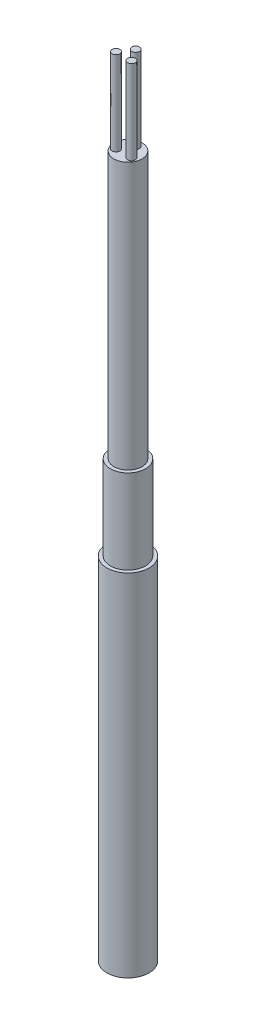
SolidWorks part; units mm, degrees
ref_plane "Front Plane" through (0, 0, 0) normal (0, 0, 1) x (1, 0, 0)
ref_plane "Top Plane" through (0, 0, 0) normal (0, 1, 0) x (1, 0, 0)
ref_plane "Right Plane" through (0, 0, 0) normal (1, 0, 0) x (0, 0, -1)
sketch "SK Stainless sheath" plane through (0, 0, 0) normal (0, 1, 0) x (1, 0, 0)
  circle A0 centre (0, 0) radius 3
extrude "Stainless sheath" add sketch "SK Stainless sheath" along normal blind 50 separate body
sketch "SK Sleeve" plane through (0, 0, 0) normal (0, 1, 0) x (1, 0, 0)
  circle A0 centre (0, 0) radius 2.5
extrude "Sleeve" add sketch "SK Sleeve" along normal blind 12 from offset 50 separate body
sketch "SK Cable" plane through (0, 0, 0) normal (0, 1, 0) x (1, 0, 0)
  circle A0 centre (0, 0) radius 2
extrude "Cable" add sketch "SK Cable" along normal blind 38 from offset 62 separate body
sketch "SK Wire red VDD" plane through (0, 0, 0) normal (0, 1, 0) x (1, 0, 0)
  circle A0 centre (-1.1, -0.6) radius 0.55
extrude "Wire red VDD" add sketch "SK Wire red VDD" along normal blind 12 from offset 100 separate body
sketch "SK Wire black GND" plane through (0, 0, 0) normal (0, 1, 0) x (1, 0, 0)
  circle A0 centre (1.1, -0.6) radius 0.55
extrude "Wire black GND" add sketch "SK Wire black GND" along normal blind 12 from offset 100 separate body
sketch "SK Wire yellow DQ" plane through (0, 0, 0) normal (0, 1, 0) x (1, 0, 0)
  circle A0 centre (0, 1.1) radius 0.55
extrude "Wire yellow DQ" add sketch "SK Wire yellow DQ" along normal blind 12 from offset 100 separate body
